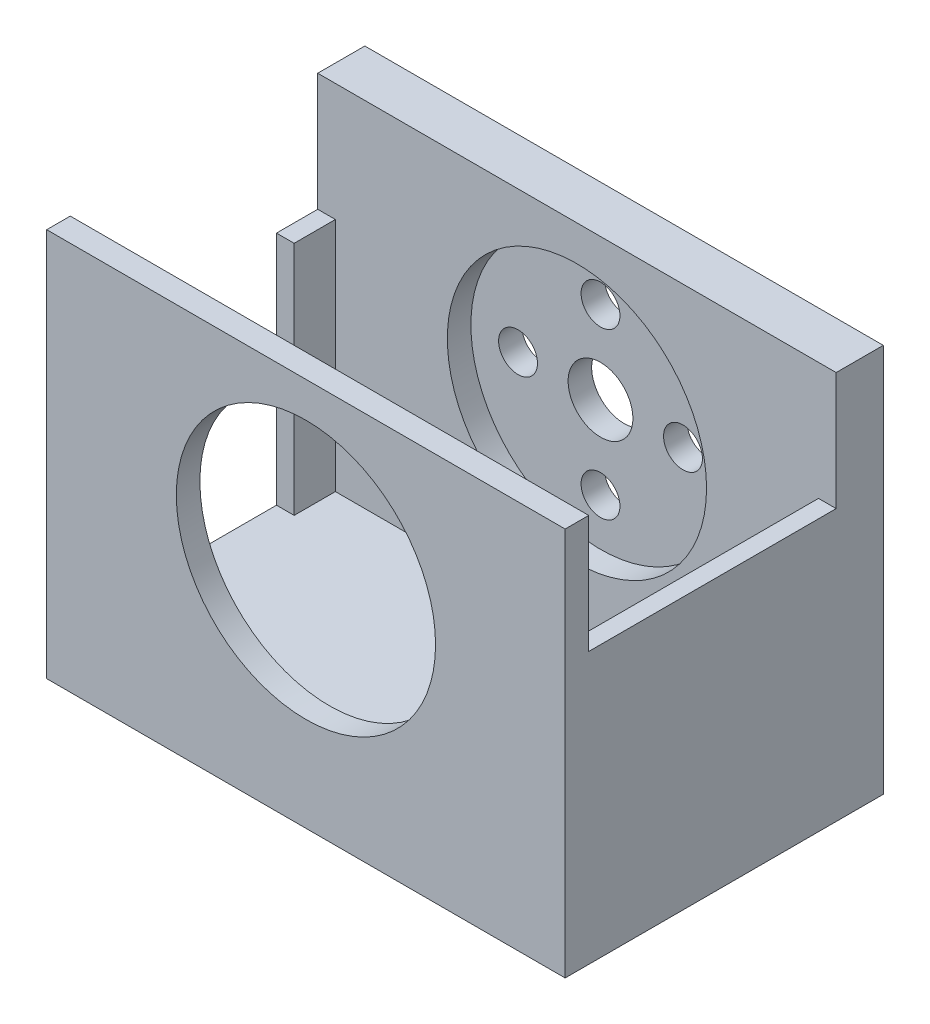
SolidWorks part; units mm, degrees
ref_plane "Front Plane" through (0, 0, 0) normal (0, 0, 1) x (1, 0, 0)
ref_plane "Top Plane" through (0, 0, 0) normal (0, 1, 0) x (1, 0, 0)
ref_plane "Right Plane" through (0, 0, 0) normal (1, 0, 0) x (0, 0, -1)
sketch "Sketch1" plane through (0, 0, 0) normal (0, 1, 0) x (1, 0, 0)
  line L0 (0, 13.5) -> (0, -13.5) construction
  line L1 (-22, 13.5) -> (22, 13.5)
  line L2 (-22, 13.5) -> (-22, -13.5)
  line L3 (-22, -13.5) -> (22, -13.5)
  line L4 (22, 13.5) -> (22, -13.5)
  point P7 (0, 0)
  dimension "D1" = 27
  dimension "D2" = 44
extrude "Boss-Extrude1" add sketch "Sketch1" along normal blind 23
sketch "Sketch2" plane through (0, 0, 0) normal (0, 1, 0) x (1, 0, 0)
  line L0 (0, 9.5) -> (0, -11.5) construction
  line L1 (-20.5, 9.5) -> (20.5, 9.5)
  line L2 (-20.5, 9.5) -> (-20.5, -11.5)
  line L3 (-20.5, -11.5) -> (20.5, -11.5)
  line L4 (20.5, 9.5) -> (20.5, -11.5)
  line L5 (22, 13.5) -> (-22, 13.5) construction
  dimension "D1" = 21
  dimension "D2" = 41
  dimension "D3" = 4
extrude "Cut-Extrude2" cut sketch "Sketch2" against normal blind 20 from surface at 23 starting at face at (0, 23, 0)
sketch "Sketch3" plane through (0, 0, 0) normal (1, 0, 0) x (0, 0, -1)
  line L0 (-13.5, 23) -> (13.5, 23) construction
  line L1 (-8, 23) -> (6, 23)
  line L2 (-8, 23) -> (-8, 3)
  line L3 (-8, 3) -> (6, 3)
  line L4 (6, 23) -> (6, 3)
  line L7 (13.5, 23) -> (13.5, 0) construction
  dimension "D1" = 20
  dimension "D2" = 14
  dimension "D3" = 7.5
extrude "Cut-Extrude3" cut sketch "Sketch3" against normal blind 20 from surface at -20.5 starting at face at (-20.5, 13, 1)
sketch "Sketch4" plane through (0, 0, 0) normal (0, 1, 0) x (1, 0, 0)
  line L0 (22, -13.5) -> (22, 13.5) construction
  line L1 (-22, 13.5) -> (22, 13.5)
  line L2 (-22, 13.5) -> (-22, 9.5)
  line L3 (-22, 9.5) -> (22, 9.5)
  line L4 (22, 13.5) -> (22, 9.5)
  line L5 (-22, -8) -> (-22, -13.5) construction
  line L6 (22, -13.5) -> (-22, -13.5)
  line L7 (22, -13.5) -> (22, -11.5)
  line L8 (22, -11.5) -> (-22, -11.5)
  line L9 (-22, -13.5) -> (-22, -11.5)
  line L10 (20.5, -11.5) -> (-20.5, -11.5) construction
  line L11 (-20.5, 9.5) -> (20.5, 9.5) construction
extrude "Boss-Extrude2" add sketch "Sketch4" along normal blind 10 from surface at 23 starting at face at (-7.0833, 23, 0.6667)
sketch "Sketch5" plane through (0, 0, 0) normal (0, 0, 1) x (1, 0, 0)
  line L0 (0, -12.65) -> (0, 12.65) construction
  line L1 (22, 33) -> (-22, 33) construction
  circle A0 centre (0, 19) radius 11
  point P4 (0, 0)
  dimension "D1" = 22
  dimension "D2" = 14
extrude "Cut-Extrude4" cut sketch "Sketch5" against normal blind 2 and the other way through all from surface at -9.5 starting at face at (0, 20.5, -9.5)
sketch "Sketch6" plane through (0, 0, 0) normal (0, 0, 1) x (1, 0, 0)
  line L0 (-11, 19) -> (11, 19) construction
  line L1 (0, -12.65) -> (0, 12.65) construction
  circle A0 centre (-7, 19) radius 1.65
  circle A1 centre (0, 19) radius 2.75
  circle A2 centre (0, 19) radius 11 construction
  circle A7 centre (0, 26) radius 1.65
  circle A8 centre (7, 19) radius 1.65
  circle A9 centre (0, 12) radius 1.65
  point P20 (0, 19)
  dimension "D1" = 5.5
  dimension "D2" = 3.3
  dimension "D3" = 7
  dimension "D4" = 4
extrude "Cut-Extrude5" cut sketch "Sketch6" along normal through all both and the other way through all
